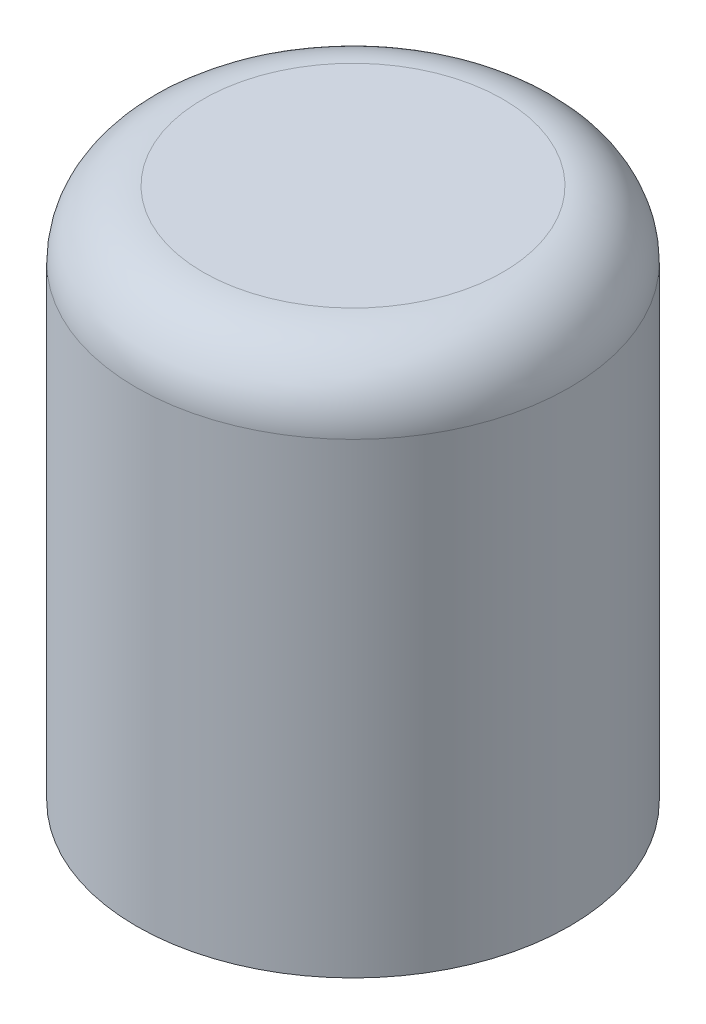
SolidWorks part; units mm, degrees
ref_plane "Front Plane" through (0, 0, 0) normal (0, 0, 1) x (1, 0, 0)
ref_plane "Top Plane" through (0, 0, 0) normal (0, 1, 0) x (1, 0, 0)
ref_plane "Right Plane" through (0, 0, 0) normal (1, 0, 0) x (0, 0, -1)
sketch "Sketch1" plane through (0, 0, 0) normal (0, 1, 0) x (1, 0, 0)
  circle A0 centre (0, 0) radius 3.25
  dimension "D1" = 6.5
extrude "Boss-Extrude1" add sketch "Sketch1" along normal blind 8
fillet "Fillet1" radius 1 1 edges at (0, 8, 3.25)
sketch "Sketch2" plane through (0, 0, 0) normal (0, -1, 0) x (1, 0, 0)
  circle A0 centre (0, 0) radius 1.65
  circle A1 centre (0, 0) radius 3.25
  circle A2 centre (0, 0) radius 3.25
  dimension "D2" = 3.3
  dimension "D1" = 0
extrude "Cut-Extrude1" cut sketch "Sketch2" against normal blind 5 draft 1.7 contours A0
